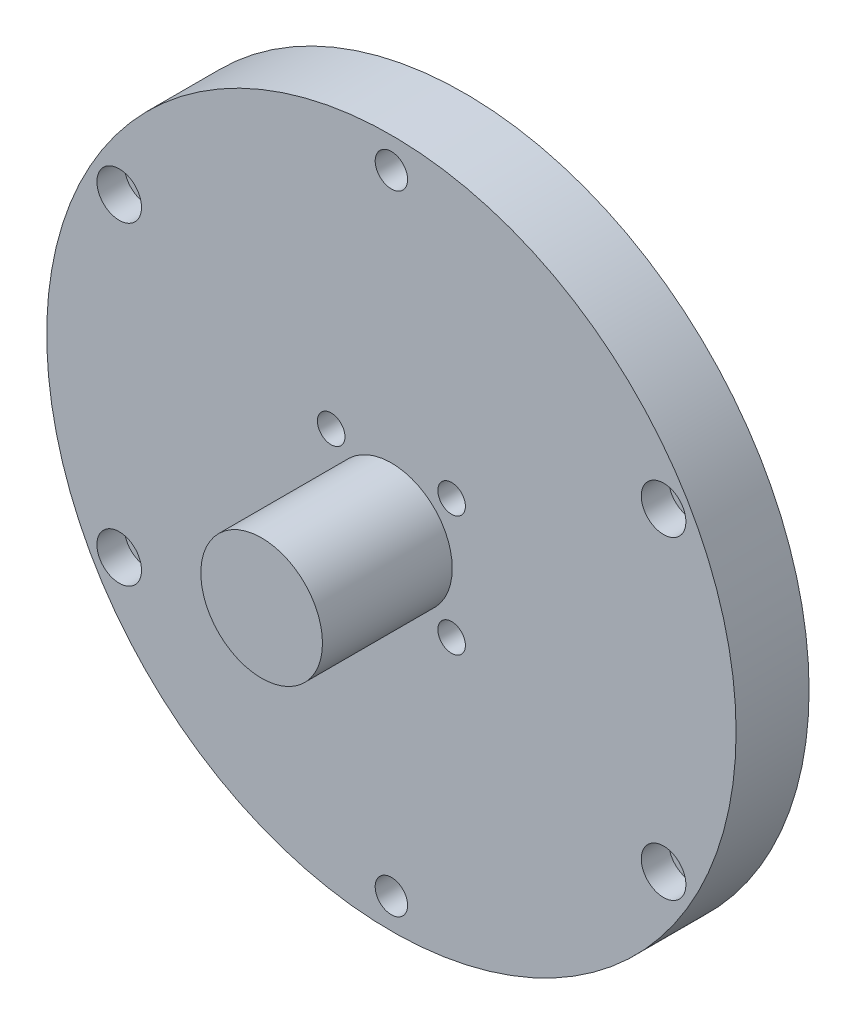
SolidWorks part; units mm, degrees
material "A6061"
ref_plane "前视基准面" through (0, 0, 0) normal (0, 0, 1) x (1, 0, 0)
ref_plane "上视基准面" through (0, 0, 0) normal (0, 1, 0) x (1, 0, 0)
ref_plane "右视基准面" through (0, 0, 0) normal (1, 0, 0) x (0, 0, -1)
sketch "草图1" plane through (0, 0, 0) normal (0, 0, 1) x (1, 0, 0)
  line L0 (-14.8492, 14.8492) -> (0, 0) construction
  line L1 (0, 0) -> (0, 30.9047) construction
  circle A0 centre (0, 0) radius 77.5 construction
  circle A1 centre (0, 0) radius 85
  circle A2 centre (0, 77.5) radius 4
  circle A3 centre (67.117, 38.75) radius 4
  circle A4 centre (67.117, -38.75) radius 4
  circle A5 centre (0, -77.5) radius 4
  circle A6 centre (-67.117, -38.75) radius 4
  circle A7 centre (-67.117, 38.75) radius 4
  circle A8 centre (0, 77.5) radius 5.5 construction
  circle A9 centre (-14.8492, 14.8492) radius 3
  circle A10 centre (0, 0) radius 21 construction
  circle A11 centre (14.8492, 14.8492) radius 3
  circle A12 centre (14.8492, -14.8492) radius 3
  circle A13 centre (-14.8492, -14.8492) radius 3
  point P19 (0, 0)
  point P30 (0, 0)
  dimension "D1" = 155
  dimension "D2" = 170
  dimension "D3" = 8
  dimension "D5" = 11
  dimension "D6" = 42
  dimension "D7" = 6
  dimension "D8" = 45
  dimension "D4" = 6
  dimension "D9" = 4
extrude "凸台-拉伸1" add sketch "草图1" along normal blind 18
hole_wizard "打孔尺寸(%根据)内六角圆柱头螺钉的类型1" positions "草图2" profile "草图3" counterbore size "M6" standard "GB" end condition through all
sketch "草图2" plane through (0, 0, 18) normal (0, 0, 1) x (1, 0, 0)
  point P0 (-67.117, 38.75)
  point P3 (67.117, 38.75)
  point P6 (67.117, -38.75)
  point P9 (-67.117, -38.75)
sketch "草图3" plane through (-67.117, 38.75, 18) normal (1, 0, 0) x (0, -1, 0)
  line L0 (0, 0) -> (0, 18)
  line L1 (0, 18) -> (3.3, 18)
  line L3 (3.3, 18) -> (3.3, 6.8)
  line L4 (3.3, 6.8) -> (5.5, 6.8)
  line L5 (5.5, 6.8) -> (5.5, 0)
  line L7 (5.5, 0) -> (0, 0)
  line L11 (0, -6.35) -> (0, 107.95) construction
  dimension "通孔孔直径" = 6.6
  dimension "通孔孔深度" = 18
  dimension "柱形沉头孔直径" = 11
  dimension "柱形沉头孔深度" = 6.8
hole_wizard "M8 螺纹孔1" positions "草图4" profile "草图5" tap size "M8" standard "GB" end condition through all
sketch "草图4" plane through (0, 0, 18) normal (0, 0, 1) x (1, 0, 0)
  point P0 (-14.8492, 14.8492)
  point P3 (14.8492, 14.8492)
  point P6 (14.8492, -14.8492)
  point P9 (-14.8492, -14.8492)
sketch "草图5" plane through (-14.8492, 14.8492, 18) normal (1, 0, 0) x (0, -1, 0)
  line L0 (0, 0) -> (0, 18)
  line L1 (0, 18) -> (3.4, 18)
  line L2 (3.4, 18) -> (3.4, 0)
  line L5 (3.4, 0) -> (0, 0)
  line L11 (0, -6.35) -> (0, 107.95) construction
  dimension "通孔螺纹孔钻头直径" = 6.8
  dimension "通孔螺纹孔钻头深度" = 18
cosmetic thread "孔螺蚊线1" parameters "D2"=8
cosmetic thread "孔螺蚊线2" parameters "D2"=8
cosmetic thread "孔螺蚊线3" parameters "D2"=8
cosmetic thread "孔螺蚊线4" parameters "D2"=8
sketch "草图6" plane through (0, 0, 18) normal (0, 0, 1) x (1, 0, 0)
  circle A0 centre (0, 0) radius 15
  dimension "D1" = 30
extrude "凸台-拉伸2" add sketch "草图6" along normal blind 32
